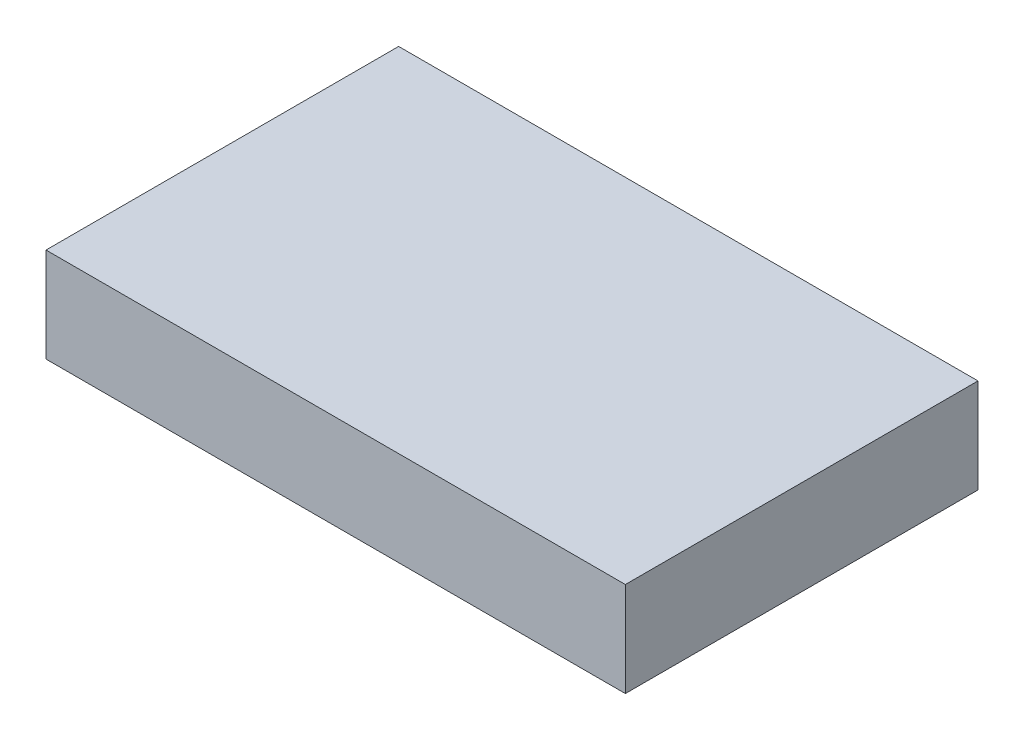
SolidWorks part; units mm, degrees
ref_plane "Front Plane" through (0, 0, 0) normal (0, 0, 1) x (1, 0, 0)
ref_plane "Top Plane" through (0, 0, 0) normal (0, 1, 0) x (1, 0, 0)
ref_plane "Right Plane" through (0, 0, 0) normal (1, 0, 0) x (0, 0, -1)
sketch "Sketch1" plane through (0, 0, 0) normal (0, 1, 0) x (1, 0, 0)
  line L1 (-266.1429, 115.8214) -> (-174.1429, 115.8214)
  line L2 (-266.1429, 115.8214) -> (-266.1429, 59.8214)
  line L3 (-266.1429, 59.8214) -> (-174.1429, 59.8214)
  line L4 (-174.1429, 115.8214) -> (-174.1429, 59.8214)
  dimension "D1" = 92
  dimension "D2" = 56
extrude "Boss-Extrude1" add sketch "Sketch1" along normal blind 15
